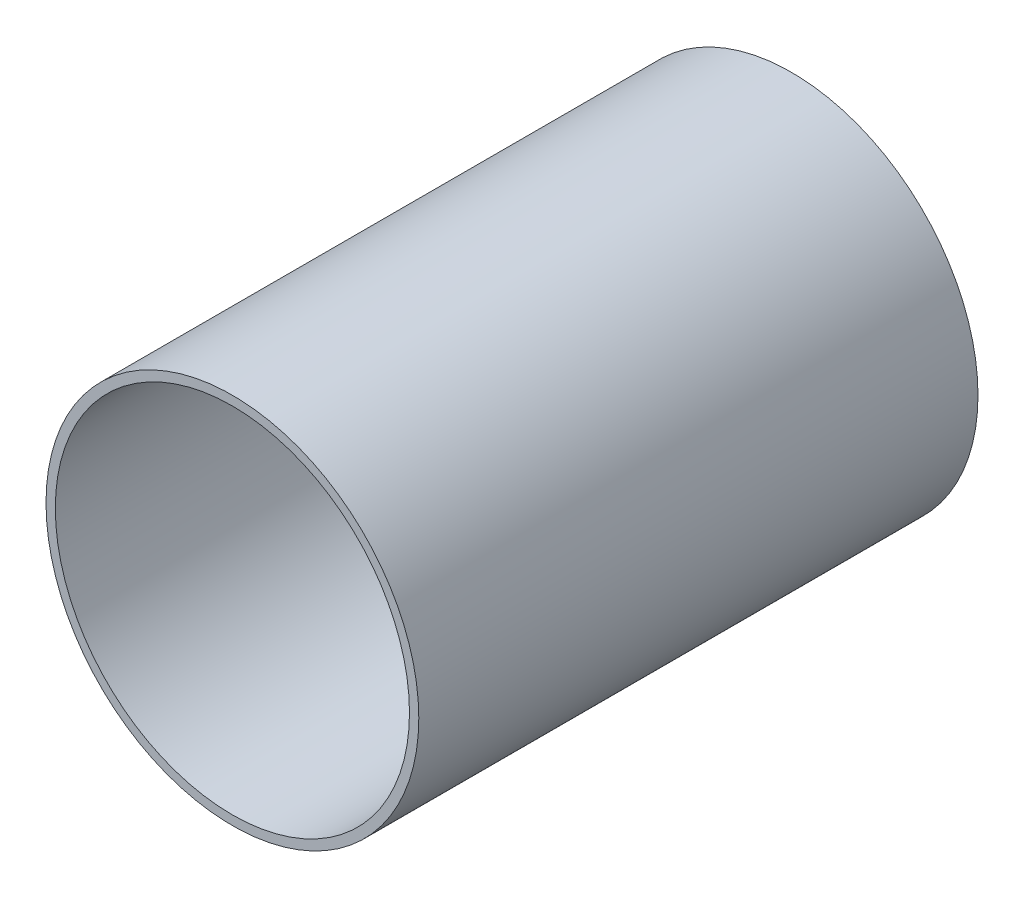
SolidWorks part; units mm, degrees
ref_plane "Piano frontale" through (0, 0, 0) normal (0, 0, 1) x (1, 0, 0)
ref_plane "Piano superiore" through (0, 0, 0) normal (0, 1, 0) x (1, 0, 0)
ref_plane "Piano destro" through (0, 0, 0) normal (1, 0, 0) x (0, 0, -1)
sketch "Schizzo1" plane through (0, 0, 0) normal (0, 0, 1) x (1, 0, 0)
  circle A0 centre (0, 11.6608) radius 100
  circle A1 centre (0, 11.6608) radius 95
  dimension "D1" = 190
  dimension "D2" = 200
extrude "Estrusione-Estrusione1" add sketch "Schizzo1" along normal blind 300
